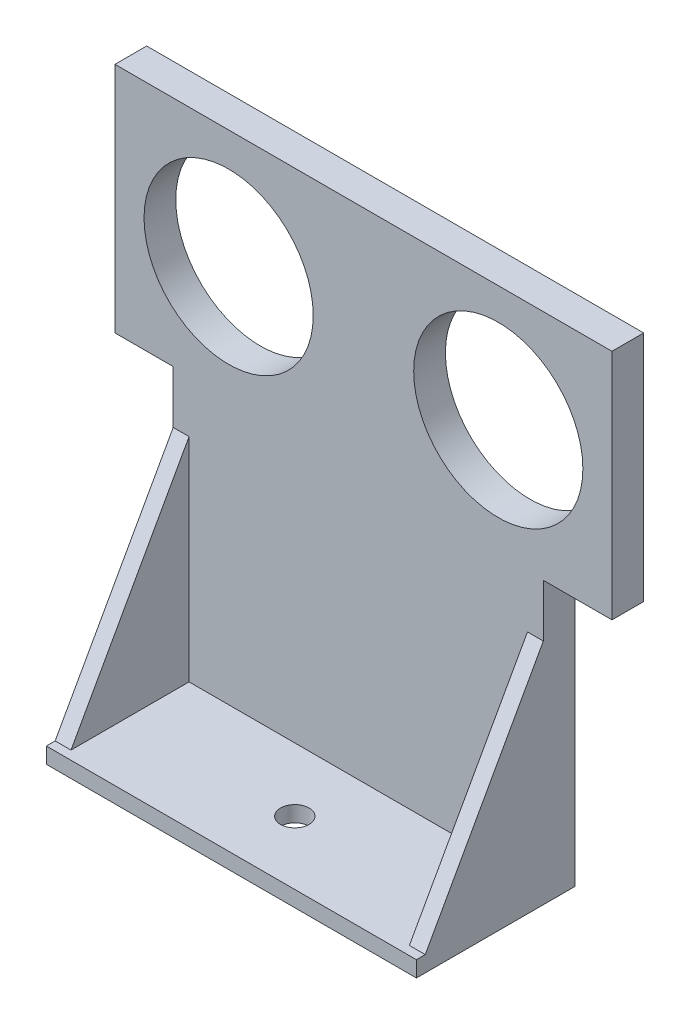
SolidWorks part; units mm, degrees
ref_plane "Front Plane" through (0, 0, 0) normal (0, 0, 1) x (1, 0, 0)
ref_plane "Top Plane" through (0, 0, 0) normal (0, 1, 0) x (1, 0, 0)
ref_plane "Right Plane" through (0, 0, 0) normal (1, 0, 0) x (0, 0, -1)
sketch "Sketch2" plane through (0, 0, 0) normal (0, 1, 0) x (1, 0, 0)
  line L0 (0, 0) -> (0, -6)
  line L1 (17.5, -6) -> (-17.5, -6)
  line L2 (17.5, -6) -> (17.5, 6)
  line L3 (17.5, 6) -> (-17.5, 6)
  line L4 (-17.5, -6) -> (-17.5, 6)
  line L5 (17.5, -6) -> (-17.5, 6) construction
  line L6 (17.5, 6) -> (-17.5, -6) construction
  circle A0 centre (0, 0) radius 1.35
  point P0 (0, 0)
  dimension "D3" = 2.7
  dimension "D1" = 35
  dimension "D2" = 12
ref_plane "Plane1" through (0, 0, -6) normal (0, 0, -1) x (-1, 0, 0)
sketch "Sketch3" plane through (0, 0, -6) normal (0, 0, -1) x (-1, 0, 0)
  line L0 (-17.5, 0) -> (17.5, 0) construction
  line L1 (17.5, 0) -> (-17.5, 0)
  line L2 (17.5, 0) -> (17.5, 26.5737)
  line L3 (17.5, 26.5737) -> (23.0098, 26.5737)
  line L4 (-17.5, 0) -> (-17.5, 26.5737)
  line L5 (-17.5, 0) -> (17.5, 0) construction
  line L7 (-23.9902, 26.5737) -> (-17.5, 26.5737)
  line L8 (-23.9902, 26.5737) -> (-23.9902, 48.5737)
  line L9 (-23.9902, 48.5737) -> (23.0098, 48.5737)
  line L10 (23.0098, 26.5737) -> (23.0098, 48.5737)
  line L11 (-23.9902, 26.5737) -> (23.0098, 48.5737) construction
  line L12 (-23.9902, 48.5737) -> (23.0098, 26.5737) construction
  circle A0 centre (-13.2402, 37.5737) radius 8
  circle A1 centre (12.2598, 37.3746) radius 8
  point P8 (-0.4902, 37.5737)
  point P10 (-0.4133, 59.9997)
  dimension "D1" = 16
  dimension "D5" = 25.5
  dimension "D6" = 16
  dimension "D2" = 22
  dimension "D3" = 47
  dimension "D4" = 10.75
  dimension "D7" = 26.5737
ref_plane "Plane2" through (17.5, 0, 0) normal (1, 0, 0) x (0, 0, -1)
sketch "Sketch4" plane through (17.5, 0, 0) normal (1, 0, 0) x (0, 0, -1)
  line L0 (6, 21.5925) -> (-6, 0)
  line L1 (-6, 0) -> (6, 0)
  line L4 (6, 0) -> (6, 21.5925)
ref_plane "Plane3" through (-17.5, 0, 0) normal (-1, 0, 0) x (0, 1, 0)
sketch "Sketch5" plane through (-17.5, 0, 0) normal (-1, 0, 0) x (0, 1, 0)
  line L0 (21.59, 6) -> (0, -6)
  line L2 (0, -6) -> (0, 6)
  line L3 (0, 6) -> (21.59, 6)
  dimension "D1" = 21.59
extrude "Boss-Extrude3" add sketch "Sketch5" against normal blind 1.5
extrude "Boss-Extrude4" add sketch "Sketch4" against normal blind 1.5 separate body contours L0 L1 L4
extrude "Boss-Extrude7" add sketch "Sketch2" along normal blind 1.5 contours A0 | L3 L4 L1 L2
extrude "Boss-Extrude8" add sketch "Sketch3" along normal blind 3 contours L9 L10 L3 L2 L1 L4 L7 L8 | A1 | A0
